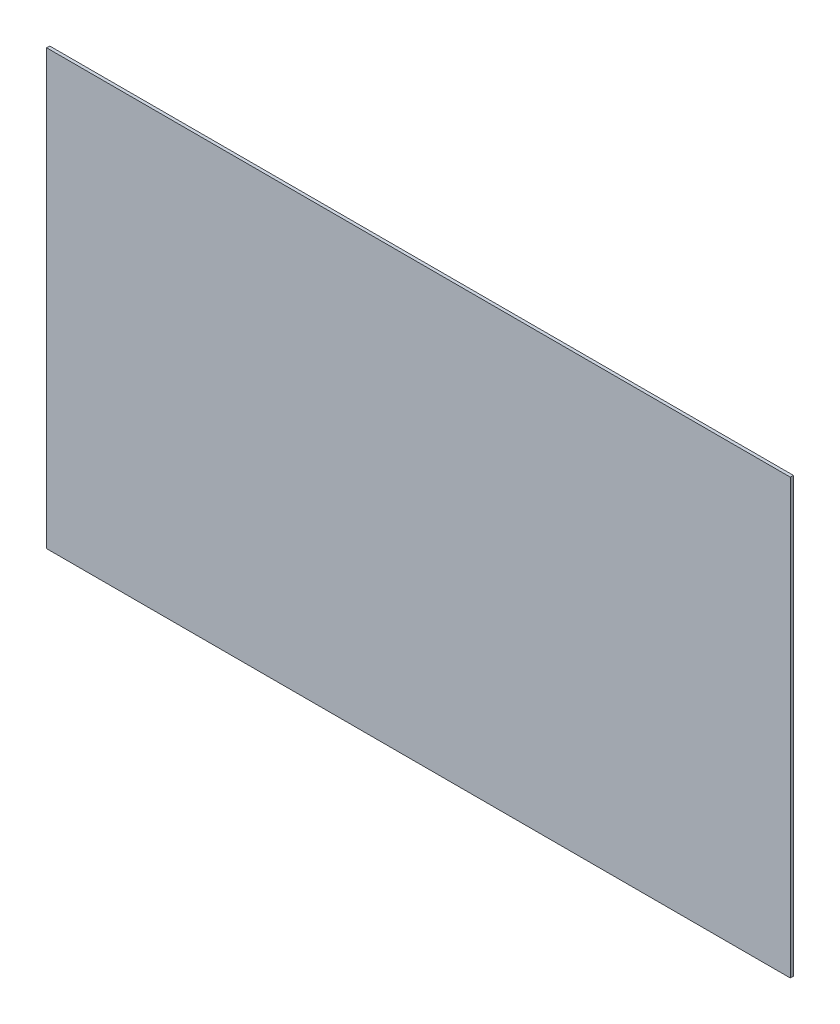
SolidWorks part; units mm, degrees
ref_plane "Front Plane" through (0, 0, 0) normal (0, 0, 1) x (1, 0, 0)
ref_plane "Top Plane" through (0, 0, 0) normal (0, 1, 0) x (1, 0, 0)
ref_plane "Right Plane" through (0, 0, 0) normal (1, 0, 0) x (0, 0, -1)
sketch "Sketch1" plane through (0, 0, 0) normal (0, 0, 1) x (1, 0, 0)
  line L0 (-360, 210) -> (360, -210) construction
  line L1 (-360, 210) -> (360, 210)
  line L2 (-360, 210) -> (-360, -210)
  line L3 (-360, -210) -> (360, -210)
  line L4 (360, 210) -> (360, -210)
  dimension "D1" = 420
  dimension "D2" = 720
extrude "Boss-Extrude1" add sketch "Sketch1" along normal blind 3
